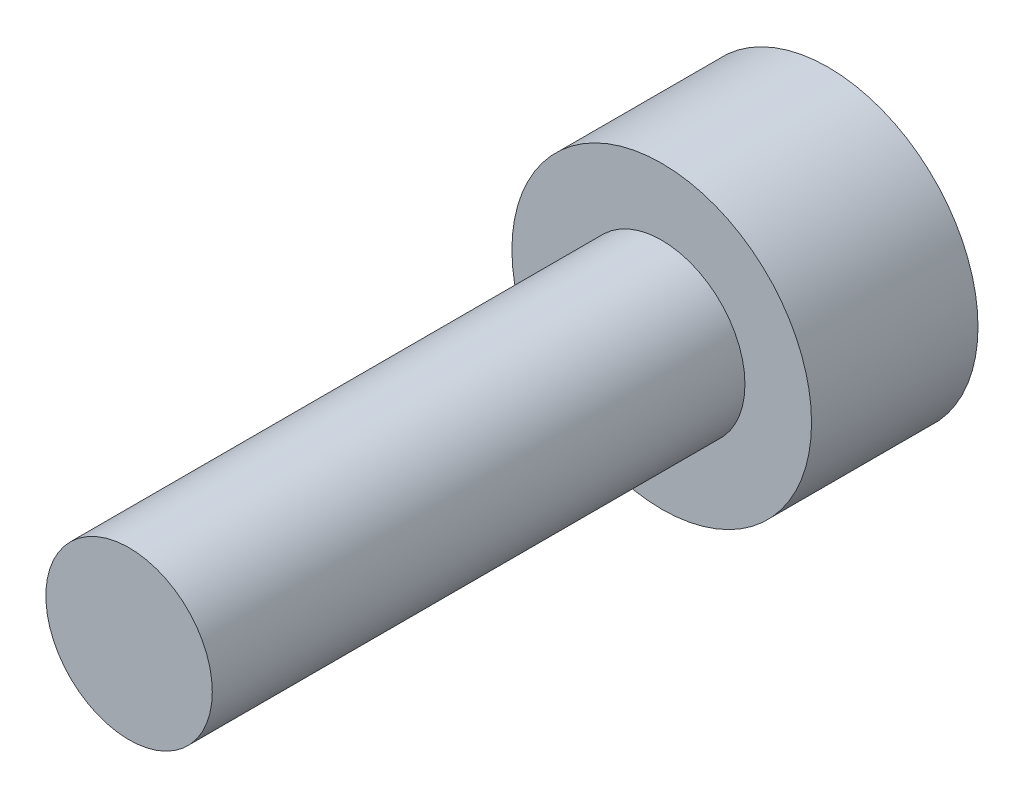
SolidWorks part; units mm, degrees
material "AISI 304"
ref_plane "Alzado" through (0, 0, 0) normal (0, 0, 1) x (1, 0, 0)
ref_plane "Planta" through (0, 0, 0) normal (0, 1, 0) x (1, 0, 0)
ref_plane "Vista lateral" through (0, 0, 0) normal (1, 0, 0) x (0, 0, -1)
sketch "Sk_Cabeza" plane through (0, 0, 0) normal (0, 0, 1) x (1, 0, 0)
  circle A0 centre (0, 0) radius 2.25
  dimension "D1" = 4.5
extrude "Cabeza" add sketch "Sk_Cabeza" along normal blind 2.5 from offset 2.5
sketch "Sk_Cuerpo" plane through (0, 0, 0) normal (0, 0, 1) x (1, 0, 0)
  circle A0 centre (0, 0) radius 1.25
  dimension "D1" = 2.5
extrude "Cuerpo" add sketch "Sk_Cuerpo" along normal blind 8
sketch "Sk_Hexagono_interior" plane through (0, 0, 0) normal (0, 0, 1) x (1, 0, 0)
  line L1 (0, -1.1547) -> (1, -0.5774)
  line L2 (1, -0.5774) -> (1, 0.5774)
  line L3 (1, 0.5774) -> (0, 1.1547)
  line L4 (0, 1.1547) -> (-1, 0.5774)
  line L5 (-1, 0.5774) -> (-1, -0.5774)
  line L6 (-1, -0.5774) -> (0, -1.1547)
  circle A0 centre (0, 0) radius 1 construction
  dimension "D1" = 2
extrude "Hexagono_interior" cut sketch "Sk_Hexagono_interior" along normal blind 1.25 from offset 2.5
